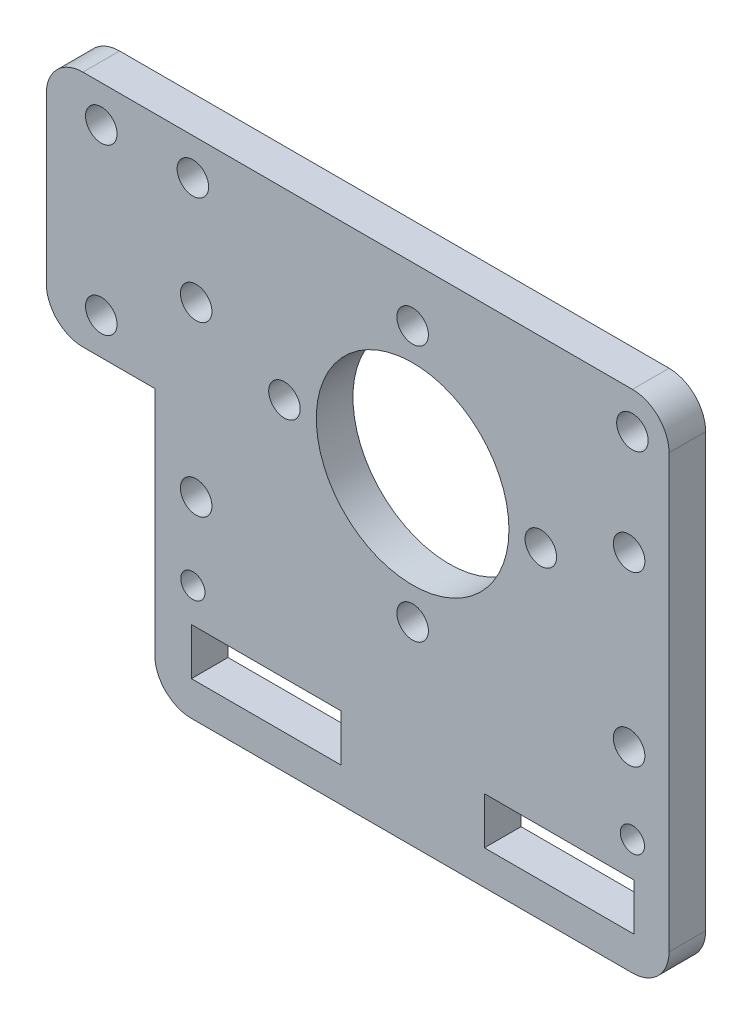
SolidWorks part; units mm, degrees
material "ﾎﾟﾘ塩化ﾋﾞﾆﾙ(PVC)硬質"
ref_plane "正面" through (0, 0, 0) normal (0, 0, 1) x (1, 0, 0)
ref_plane "平面" through (0, 0, 0) normal (0, 1, 0) x (1, 0, 0)
ref_plane "右側面" through (0, 0, 0) normal (1, 0, 0) x (0, 0, -1)
sketch "ｽｹｯﾁ1" plane through (0, 0, 0) normal (0, 0, 1) x (1, 0, 0)
  line L0 (0, 0) -> (0, 17.5) construction
  line L1 (-13.15, 0) -> (13.15, 0) construction
  line L2 (-35, 25) -> (35, 25)
  line L3 (-35, 25) -> (-35, -44)
  line L4 (-35, -44) -> (35, -44)
  line L6 (0, 25) -> (0, -44) construction
  line L7 (-9.8, -39.3) -> (-9.8, -32.9)
  line L8 (-35, -23.2) -> (35, -23.2) construction
  line L9 (-35, -23.2) -> (-35, -18) construction
  line L10 (-35, -18) -> (35, -18) construction
  line L11 (35, -23.2) -> (35, -18) construction
  line L12 (-35, -23.2) -> (35, -18) construction
  line L13 (-35, -18) -> (35, -23.2) construction
  line L14 (-35, -33.2) -> (35, -33.2) construction
  line L15 (-35, -33.2) -> (-35, -23.2) construction
  line L16 (-35, -23.2) -> (35, -23.2) construction
  line L17 (35, -33.2) -> (35, -23.2) construction
  line L18 (-35, -33.2) -> (35, -23.2) construction
  line L19 (-35, -23.2) -> (35, -33.2) construction
  line L20 (10, -39) -> (30, -39) construction
  line L21 (10, -39) -> (10, -33.2) construction
  line L22 (10, -33.2) -> (30, -33.2) construction
  line L23 (30, -39) -> (30, -33.2) construction
  line L24 (10, -39) -> (30, -33.2) construction
  line L25 (10, -33.2) -> (30, -39) construction
  line L26 (9.8, -39.3) -> (30.2, -39.3)
  line L27 (9.8, -39.3) -> (9.8, -32.9)
  line L28 (9.8, -32.9) -> (30.2, -32.9)
  line L29 (30.2, -39.3) -> (30.2, -32.9)
  line L30 (9.8, -39.3) -> (30.2, -32.9) construction
  line L31 (9.8, -32.9) -> (30.2, -39.3) construction
  line L32 (-9.8, -39.3) -> (-30.2, -39.3)
  line L33 (-30.2, -39.3) -> (-30.2, -32.9)
  line L34 (-9.8, -32.9) -> (-30.2, -32.9)
  line L35 (-35, -28.2) -> (35, -28.2) construction
  line L36 (29.55, 10.5) -> (29.55, -22.5) construction
  line L37 (-35, -9.5) -> (-42.5, -9.5) construction
  line L41 (35, -44) -> (35, 25)
  line L42 (24.1, -22.5) -> (35, -22.5) construction
  line L43 (24.1, -22.5) -> (24.1, 10.5) construction
  line L44 (24.1, 10.5) -> (35, 10.5) construction
  line L45 (-50, -44) -> (-35, -44)
  line L46 (-50, -44) -> (-50, 25)
  line L47 (-50, 25) -> (-35, 25)
  line L48 (-35, -44) -> (-35, 25)
  line L49 (-50, -44) -> (-35, 25) construction
  line L50 (-50, 25) -> (-35, -44) construction
  line L51 (35, -22.5) -> (35, 10.5) construction
  line L52 (24.1, -22.5) -> (35, 10.5) construction
  line L53 (24.1, 10.5) -> (35, -22.5) construction
  line L54 (24.1, -6) -> (35, -6) construction
  line L55 (-42.5, 25) -> (-42.5, -44) construction
  circle A0 centre (0, 0) radius 13.15
  circle A1 centre (0, 0) radius 17.5 construction
  circle A2 centre (0, 17.5) radius 2.15
  circle A3 centre (17.5, 0) radius 2.15
  circle A4 centre (0, -17.5) radius 2.15
  circle A5 centre (-17.5, 0) radius 2.15
  circle A10 centre (0, 0) radius 18 construction
  circle A11 centre (30, -28.2) radius 1.65
  circle A12 centre (-30, -28.2) radius 1.65
  circle A13 centre (30, 20) radius 2.15
  circle A14 centre (-30, 20) radius 2.15
  circle A17 centre (29.55, -17.5) radius 2.15
  circle A18 centre (29.55, 5.5) radius 2.15
  circle A19 centre (-29.55, -17.5) radius 2.15
  circle A20 centre (-29.55, 5.5) radius 2.15
  circle A21 centre (-42.5, 20) radius 2.15
  circle A23 centre (-42.5, -2.5) radius 2.15
  point P14 (0, 0)
  point P23 (20, -36.1)
  point P30 (0, -20.6)
  point P35 (0, -28.2)
  point P36 (20, -36.1)
  point P57 (29.55, -6)
  dimension "D1" = 26.3
  dimension "D2" = 35
  dimension "D3" = 4.3
  dimension "D4" = 4
  dimension "D5" = 25
  dimension "D6" = 5.2
  dimension "D7" = 5
  dimension "D8" = 3.3
  dimension "D9" = 5
  dimension "D10" = 5
  dimension "D11" = 4.3
  dimension "D14" = 5
  dimension "D15" = 15
  dimension "D16" = 5
  dimension "D17" = 4.3
  dimension "D18" = 36
  dimension "D21" = 41.5
  dimension "D27" = 26.5
  dimension "D28" = 5
  dimension "D30" = 23
  dimension "D31" = 4.3
  dimension "D12" = 5.8
  dimension "D13" = 70
  dimension "D19" = 10
  dimension "D20" = 20
  dimension "D22" = 5
  dimension "D23" = 6.4
  dimension "D24" = 20.4
  dimension "D29" = 10.9
extrude "ﾎﾞｽ - 押し出し1" add sketch "ｽｹｯﾁ1" along normal blind 5
sketch "ｽｹｯﾁ2" plane through (0, 0, 5) normal (0, 0, 1) x (1, 0, 0)
  line L1 (-50, -44) -> (-50, 25) construction
  line L2 (-50, -44) -> (35, -44) construction
  line L3 (-35.2, -44) -> (-50, -44)
  line L4 (-50, -44) -> (-50, -7.5)
  line L5 (-30.2, -39.3) -> (-30.2, -32.9) construction
  line L6 (-50, -7.5) -> (-35.2, -7.5)
  line L7 (-35.2, -7.5) -> (-35.2, -44)
  dimension "D1" = 36.5
  dimension "D2" = 5
extrude "ｶｯﾄ - 押し出し1" cut sketch "ｽｹｯﾁ2" against normal through all
fillet "ﾌｨﾚｯﾄ1" radius 5 5 edges at (35, -44, 2.5) (35, 25, 2.5) (-50, 25, 2.5) (-35.2, -44, 2.5) (-50, -7.5, 2.5)
